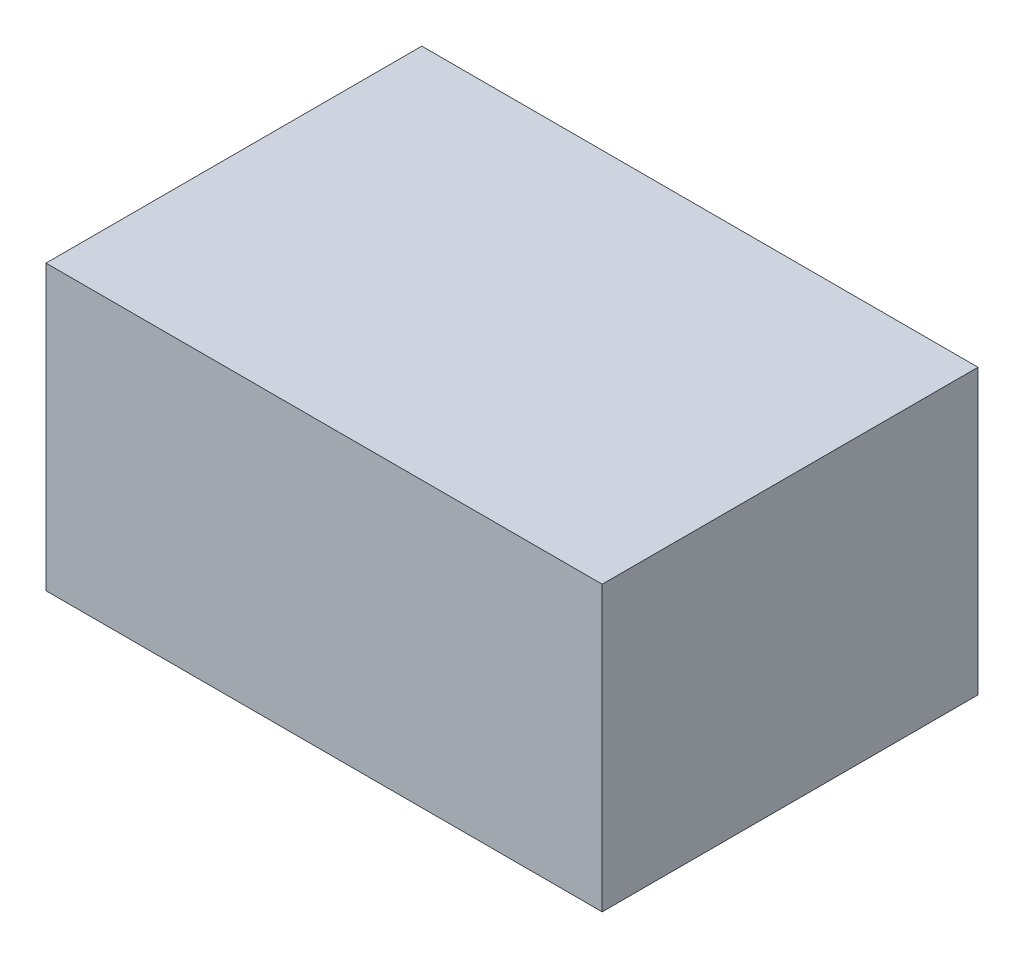
SolidWorks part; units mm, degrees
ref_plane "Front Plane" through (0, 0, 0) normal (0, 0, 1) x (1, 0, 0)
ref_plane "Top Plane" through (0, 0, 0) normal (0, 1, 0) x (1, 0, 0)
ref_plane "Right Plane" through (0, 0, 0) normal (1, 0, 0) x (0, 0, -1)
sketch "Sketch1" plane through (0, 0, 0) normal (0, 1, 0) x (1, 0, 0)
  line L1 (-30.4439, 16.6102) -> (67.5575, 16.6102)
  line L2 (-30.4439, 16.6102) -> (-30.4439, -49.6063)
  line L3 (-30.4439, -49.6063) -> (67.5575, -49.6063)
  line L4 (67.5575, 16.6102) -> (67.5575, -49.6063)
extrude "Boss-Extrude1" add sketch "Sketch1" along normal blind 50
